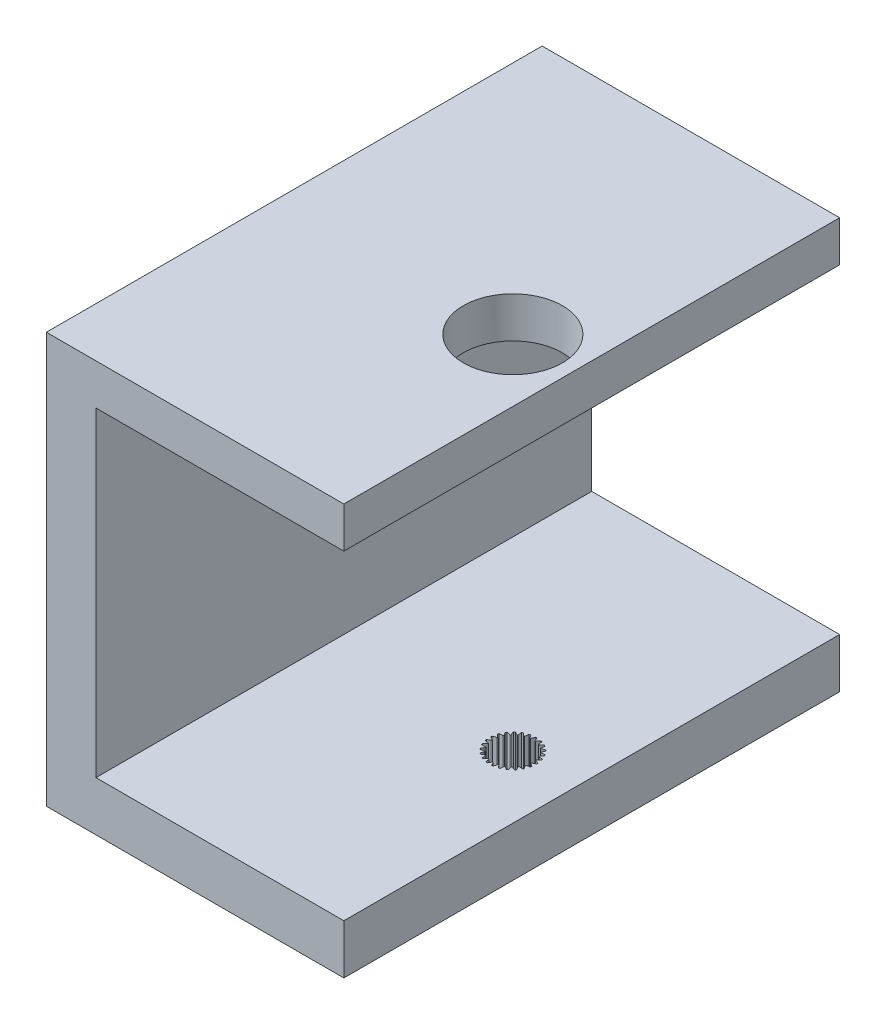
SolidWorks part; units mm, degrees
ref_plane "Front Plane" through (0, 0, 0) normal (0, 0, 1) x (1, 0, 0)
ref_plane "Top Plane" through (0, 0, 0) normal (0, 1, 0) x (1, 0, 0)
ref_plane "Right Plane" through (0, 0, 0) normal (1, 0, 0) x (0, 0, -1)
sketch "Sketch1" plane through (0, 0, 0) normal (0, 0, 1) x (1, 0, 0)
  line L0 (-37.15, -39.05) -> (-37.15, 7.178)
  line L5 (-37.15, 7.178) -> (-37.15, 13.528)
  line L6 (-37.15, 13.528) -> (45.4, 13.528)
  line L7 (20, 8.3) -> (45.4, 8.3)
  line L8 (20, 8.3) -> (-30.8, 8.3)
  line L12 (45.4, 13.528) -> (45.4, 8.3)
  line L13 (20, -32.7) -> (45.4, -32.7)
  line L14 (45.4, -32.7) -> (45.4, -39.05)
  line L15 (-30.8, -39.05) -> (45.4, -39.05)
  line L17 (20, -32.7) -> (-30.8, -32.7)
  line L18 (-30.8, 8.3) -> (-30.8, -32.7)
  line L20 (-30.8, -39.05) -> (-37.15, -39.05)
extrude "Boss-Extrude2" add sketch "Sketch1" along normal blind 63.5 contours L8 L18 L17 L13 L14 L15 L20 L0 L5 L6 L12 L7
sketch "Sketch2" plane through (0, 13.528, 0) normal (0, 1, 0) x (1, 0, 0)
  line L1 (-37.15, 0) -> (45.4, 0) construction
  line L2 (0.95, 0) -> (0.95, -63.5)
  line L3 (-37.15, -63.5) -> (45.4, -63.5) construction
  line L4 (0.95, -63.5) -> (45.4, -63.5)
  line L5 (45.4, -63.5) -> (45.4, 0)
  line L6 (45.4, 0) -> (0.95, 0)
extrude "Cut-Extrude1" cut sketch "Sketch2" against normal blind 63.5
sketch "Sketch4" plane through (0, 13.528, 0) normal (0, 1, 0) x (1, 0, 0)
  line L0 (0.95, -31.75) -> (-7.05, -31.75) construction
  line L1 (0.95, 0) -> (0.95, -63.5) construction
  line L2 (-7.05, -63.5) -> (-7.05, -33.85) construction
  line L4 (-37.15, -63.5) -> (0.95, -63.5) construction
  circle A0 centre (-7.05, -33.85) radius 6.35
extrude "Cut-Extrude2" cut sketch "Sketch4" against normal blind 63.5 contours A0
sketch "Sketch5" plane through (0, -32.7, 0) normal (0, 1, 0) x (1, 0, 0)
  line L0 (-7.1187, -30.8498) -> (-7.3272, -31.323)
  line L1 (-7.1187, -30.8498) -> (-6.9378, -30.8524)
  line L2 (-6.3756, -30.9307) -> (-6.6953, -31.3372)
  line L3 (-6.3756, -30.9307) -> (-6.2011, -30.9782)
  line L4 (-5.6761, -31.1939) -> (-6.0868, -31.5081)
  line L5 (-5.6761, -31.1939) -> (-5.5189, -31.2833)
  line L6 (-5.064, -31.6228) -> (-5.5399, -31.825)
  line L7 (-5.064, -31.6228) -> (-4.9339, -31.7485)
  line L8 (-4.5777, -32.1904) -> (-5.089, -32.2679)
  line L9 (-4.5777, -32.1904) -> (-4.4831, -32.3445)
  line L10 (-4.2479, -32.8611) -> (-4.7624, -32.809)
  line L11 (-4.2479, -32.8611) -> (-4.1946, -33.0339)
  line L12 (-4.0953, -33.5928) -> (-4.5807, -33.4144)
  line L13 (-4.0953, -33.5928) -> (-4.0866, -33.7734)
  line L14 (-4.1294, -34.3394) -> (-4.5552, -34.0459)
  line L15 (-4.1294, -34.3394) -> (-4.1659, -34.5166)
  line L16 (-4.3482, -35.0541) -> (-4.6876, -34.6639)
  line L17 (-4.3482, -35.0541) -> (-4.4275, -35.2166)
  line L18 (-4.7377, -35.692) -> (-4.9695, -35.2296)
  line L19 (-4.7377, -35.692) -> (-4.855, -35.8296)
  line L20 (-5.2737, -36.2129) -> (-5.3832, -35.7074)
  line L21 (-5.2737, -36.2129) -> (-5.4216, -36.317)
  line L22 (-5.9224, -36.5841) -> (-5.9027, -36.0674)
  line L23 (-5.9224, -36.5841) -> (-6.0915, -36.6483)
  line L24 (-6.6431, -36.7824) -> (-6.4955, -36.2868)
  line L25 (-6.6431, -36.7824) -> (-6.8228, -36.8025)
  line L26 (-7.3904, -36.7952) -> (-7.1242, -36.3519)
  line L27 (-7.3904, -36.7952) -> (-7.5694, -36.77)
  line L28 (-8.1174, -36.6218) -> (-7.7493, -36.2586)
  line L29 (-8.1174, -36.6218) -> (-8.2845, -36.5528)
  line L30 (-8.7784, -36.273) -> (-8.3316, -36.0127)
  line L31 (-8.7784, -36.273) -> (-8.9232, -36.1646)
  line L32 (-9.332, -35.7708) -> (-8.8344, -35.6298)
  line L33 (-9.332, -35.7708) -> (-9.4452, -35.6298)
  line L34 (-9.7432, -35.1467) -> (-9.2262, -35.1339)
  line L35 (-9.7432, -35.1467) -> (-9.8178, -34.982)
  line L36 (-9.9863, -34.44) -> (-9.4824, -34.5561)
  line L37 (-9.9863, -34.44) -> (-10.0176, -34.2618)
  line L38 (-10.0461, -33.6949) -> (-9.5869, -33.9328)
  line L39 (-10.0461, -33.6949) -> (-10.0321, -33.5146)
  line L40 (-9.9186, -32.9585) -> (-9.533, -33.303)
  line L41 (-9.9186, -32.9585) -> (-9.8603, -32.7873)
  line L42 (-9.6121, -32.2768) -> (-9.3242, -32.7065)
  line L43 (-9.6121, -32.2768) -> (-9.5129, -32.1256)
  line L44 (-9.1456, -31.6928) -> (-8.9737, -32.1806)
  line L45 (-9.1456, -31.6928) -> (-9.012, -31.571)
  line L46 (-8.5486, -31.2432) -> (-8.5033, -31.7584)
  line L47 (-8.5486, -31.2432) -> (-8.3888, -31.1584)
  line L48 (-7.8585, -30.9562) -> (-7.9427, -31.4664)
  line L49 (-7.8585, -30.9562) -> (-7.6826, -30.9138)
  line L50 (-7.05, -27.5) -> (-7.05, -40.2) construction
  circle A0 centre (-7.05, -33.85) radius 6.35 construction
  arc A2 (-7.4383, -31.2721) -> (-7.3272, -31.323) centre (-7.3435, -31.2118) ccw
  arc A3 (-6.7903, -31.2603) -> (-6.6953, -31.3372) centre (-6.6834, -31.2254) ccw
  arc A4 (-6.1597, -31.41) -> (-6.0868, -31.5081) centre (-6.0475, -31.4028) ccw
  arc A5 (-5.5861, -31.7118) -> (-5.5399, -31.825) centre (-5.4756, -31.7327) ccw
  arc A6 (-5.1056, -32.1468) -> (-5.089, -32.2679) centre (-5.0038, -32.1945) ccw
  arc A7 (-4.7484, -32.6876) -> (-4.7624, -32.809) centre (-4.6617, -32.7592) ccw
  arc A8 (-4.5369, -33.3002) -> (-4.5807, -33.4144) centre (-4.4707, -33.3911) ccw
  arc A9 (-4.4844, -33.9463) -> (-4.5552, -34.0459) centre (-4.4429, -34.0508) ccw
  arc A10 (-4.5942, -34.585) -> (-4.6876, -34.6639) centre (-4.58, -34.6966) ccw
  arc A11 (-4.8594, -35.1764) -> (-4.9695, -35.2296) centre (-4.8733, -35.288) ccw
  arc A12 (-5.2633, -35.6833) -> (-5.3832, -35.7074) centre (-5.3046, -35.7879) ccw
  arc A13 (-5.7807, -36.0738) -> (-5.9027, -36.0674) centre (-5.8466, -36.1648) ccw
  arc A14 (-6.3788, -36.3233) -> (-6.4955, -36.2868) centre (-6.4654, -36.3951) ccw
  arc A15 (-7.0202, -36.4163) -> (-7.1242, -36.3519) centre (-7.1219, -36.4643) ccw
  arc A16 (-7.6647, -36.3468) -> (-7.7493, -36.2586) centre (-7.7751, -36.368) ccw
  arc A17 (-8.2715, -36.1193) -> (-8.3316, -36.0127) centre (-8.3838, -36.1123) ccw
  arc A18 (-8.8028, -35.7479) -> (-8.8344, -35.6298) centre (-8.9097, -35.7133) ccw
  arc A19 (-9.2249, -35.2562) -> (-9.2262, -35.1339) centre (-9.32, -35.196) ccw
  arc A20 (-9.5116, -34.6749) -> (-9.4824, -34.5561) centre (-9.5887, -34.593) ccw
  arc A21 (-9.6446, -34.0405) -> (-9.5869, -33.9328) centre (-9.6989, -33.942) ccw
  arc A22 (-9.6158, -33.393) -> (-9.533, -33.303) centre (-9.6439, -33.2841) ccw
  arc A23 (-9.4268, -32.7731) -> (-9.3242, -32.7065) centre (-9.4269, -32.6606) ccw
  arc A24 (-9.0895, -32.2196) -> (-8.9737, -32.1806) centre (-9.0617, -32.1106) ccw
  arc A25 (-8.6252, -31.7673) -> (-8.5033, -31.7584) centre (-8.5712, -31.6687) ccw
  arc A26 (-8.0631, -31.4448) -> (-7.9427, -31.4664) centre (-7.9862, -31.3627) ccw
  spline S0 degree 2 poles (-7.6826, -30.9138) (-7.552, -31.0935) (-7.4383, -31.2721) knots 0 0 0 1 1 1
  spline S2 degree 2 poles (-6.9378, -30.8524) (-6.8695, -31.064) (-6.7903, -31.2603) knots 0 0 0 1 1 1
  spline S4 degree 2 poles (-6.2011, -30.9782) (-6.1876, -31.2001) (-6.1597, -31.41) knots 0 0 0 1 1 1
  spline S5 degree 2 poles (-5.5189, -31.2833) (-5.5609, -31.5016) (-5.5861, -31.7118) knots 0 0 0 1 1 1
  spline S6 degree 2 poles (-4.9339, -31.7485) (-5.029, -31.9495) (-5.1056, -32.1468) knots 0 0 0 1 1 1
  spline S7 degree 2 poles (-4.4831, -32.3445) (-4.6251, -32.5155) (-4.7484, -32.6876) knots 0 0 0 1 1 1
  spline S8 degree 2 poles (-4.1946, -33.0339) (-4.3746, -33.1643) (-4.5369, -33.3002) knots 0 0 0 1 1 1
  spline S9 degree 2 poles (-4.0866, -33.7734) (-4.2934, -33.8549) (-4.4844, -33.9463) knots 0 0 0 1 1 1
  spline S10 degree 2 poles (-4.1659, -34.5166) (-4.3865, -34.544) (-4.5942, -34.585) knots 0 0 0 1 1 1
  spline S11 degree 2 poles (-4.4275, -35.2166) (-4.648, -35.1884) (-4.8594, -35.1764) knots 0 0 0 1 1 1
  spline S12 degree 2 poles (-4.855, -35.8296) (-5.0616, -35.7474) (-5.2633, -35.6833) knots 0 0 0 1 1 1
  spline S13 degree 2 poles (-5.4216, -36.317) (-5.6012, -36.186) (-5.7807, -36.0738) knots 0 0 0 1 1 1
  spline S14 degree 2 poles (-6.0915, -36.6483) (-6.2329, -36.4767) (-6.3788, -36.3233) knots 0 0 0 1 1 1
  spline S15 degree 2 poles (-6.8228, -36.8025) (-6.9171, -36.6011) (-7.0202, -36.4163) knots 0 0 0 1 1 1
  spline S16 degree 2 poles (-7.5694, -36.77) (-7.6107, -36.5515) (-7.6647, -36.3468) knots 0 0 0 1 1 1
  spline S17 degree 2 poles (-8.2845, -36.5528) (-8.2702, -36.331) (-8.2715, -36.1193) knots 0 0 0 1 1 1
  spline S18 degree 2 poles (-8.9232, -36.1646) (-8.8541, -35.9533) (-8.8028, -35.7479) knots 0 0 0 1 1 1
  spline S19 degree 2 poles (-9.4452, -35.6298) (-9.3257, -35.4423) (-9.2249, -35.2562) knots 0 0 0 1 1 1
  spline S20 degree 2 poles (-9.8178, -34.982) (-9.6555, -34.8301) (-9.5116, -34.6749) knots 0 0 0 1 1 1
  spline S21 degree 2 poles (-10.0176, -34.2618) (-9.8226, -34.1551) (-9.6446, -34.0405) knots 0 0 0 1 1 1
  spline S22 degree 2 poles (-10.0321, -33.5146) (-9.8167, -33.4597) (-9.6158, -33.393) knots 0 0 0 1 1 1
  spline S23 degree 2 poles (-9.8603, -32.7873) (-9.638, -32.7877) (-9.4268, -32.7731) knots 0 0 0 1 1 1
  spline S24 degree 2 poles (-9.5129, -32.1256) (-9.2977, -32.1812) (-9.0895, -32.2196) knots 0 0 0 1 1 1
  spline S25 degree 2 poles (-9.012, -31.571) (-8.8174, -31.6784) (-8.6252, -31.7673) knots 0 0 0 1 1 1
  spline S26 degree 2 poles (-8.3888, -31.1584) (-8.227, -31.3109) (-8.0631, -31.4448) knots 0 0 0 1 1 1
  point P160 (-7.0675, -33.8311)
  dimension "D1" = 25
sketch "Sketch6" plane through (0, -39.05, 0) normal (0, -1, 0) x (1, 0, 0)
  line L0 (-7.05, 27.5) -> (-7.05, 40.2) construction
  circle A0 centre (-7.05, 33.85) radius 6.35
extrude "Boss-Extrude3" add sketch "Sketch6" against normal blind 6.35
extrude "Cut-Extrude3" cut sketch "Sketch5" against normal blind 6.35
